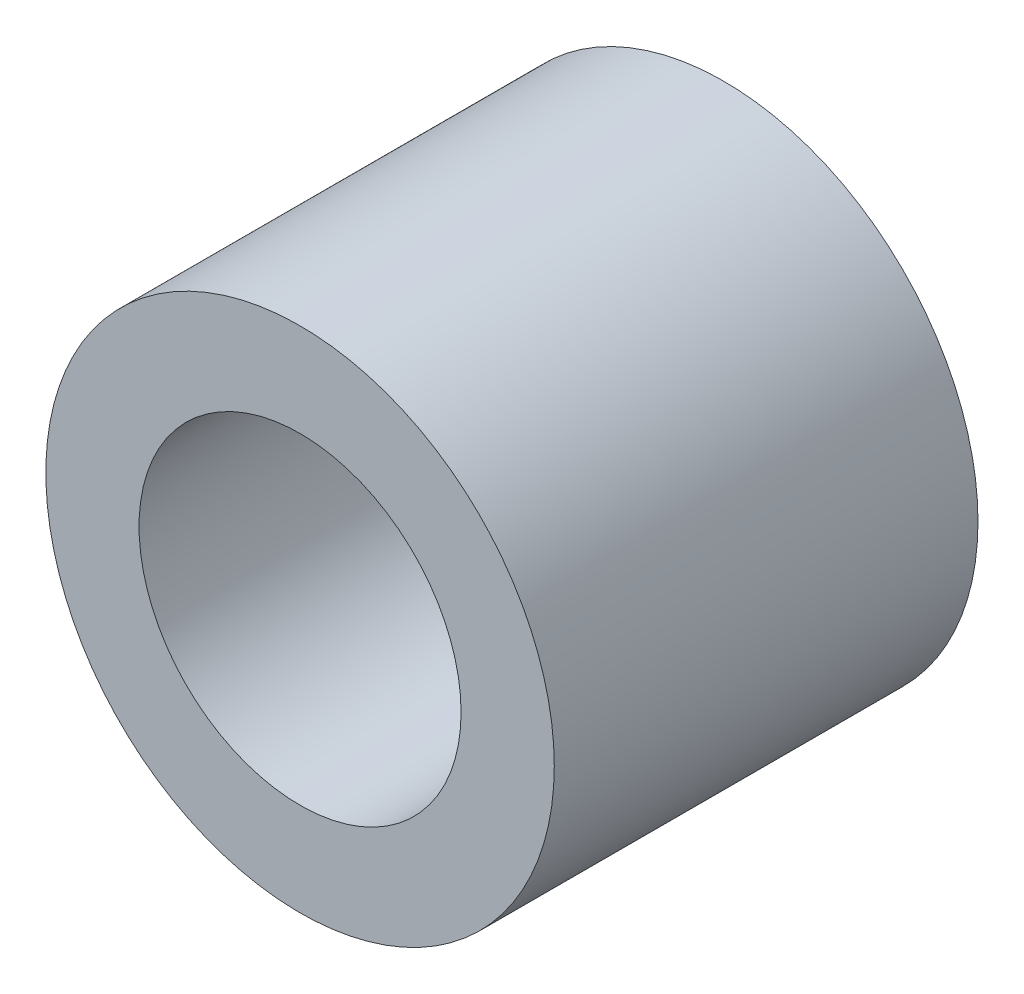
SolidWorks part; units mm, degrees
ref_plane "正面" through (0, 0, 0) normal (0, 0, 1) x (1, 0, 0)
ref_plane "平面" through (0, 0, 0) normal (0, 1, 0) x (1, 0, 0)
ref_plane "右側面" through (0, 0, 0) normal (1, 0, 0) x (0, 0, -1)
sketch "ｽｹｯﾁ1" plane through (0, 0, 0) normal (0, 0, 1) x (1, 0, 0)
  circle A0 centre (0, 0) radius 3
  circle A1 centre (0, 0) radius 1.9
  dimension "D1" = 3.8
  dimension "D2" = 6
extrude "ﾎﾞｽ - 押し出し1" add sketch "ｽｹｯﾁ1" along normal blind 5
